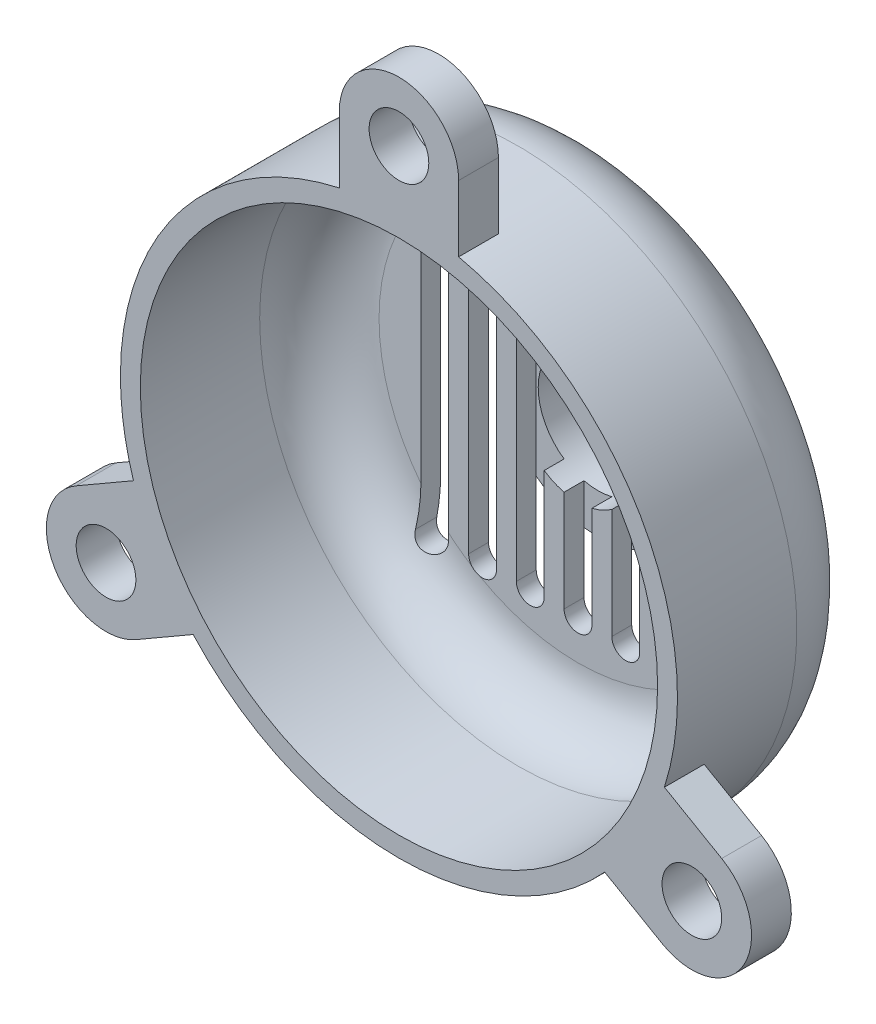
SolidWorks part; units mm, degrees
ref_plane "Front Plane" through (0, 0, 0) normal (0, 0, 1) x (1, 0, 0)
ref_plane "Top Plane" through (0, 0, 0) normal (0, 1, 0) x (1, 0, 0)
ref_plane "Right Plane" through (0, 0, 0) normal (1, 0, 0) x (0, 0, -1)
sketch "Sketch1" plane through (0, 0, 0) normal (0, 1, 0) x (1, 0, 0)
  line L0 (0, 4.1155) -> (0, -4.1155) construction
  line L1 (-7.037, 0) -> (6.2623, 0) construction
  line L2 (0, 0) -> (2.5, 0)
  line L3 (3.5, -1) -> (3.5, -2.5)
  line L4 (0, -0.25) -> (2.5, -0.25)
  line L5 (3.25, -1) -> (3.25, -2.5)
  line L6 (3.25, -2.5) -> (3.5, -2.5)
  line L7 (0, 0) -> (0, -0.25)
  arc A0 (2.5, 0) -> (3.5, -1) centre (2.5, -1) cw
  arc A1 (2.5, -0.25) -> (3.25, -1) centre (2.5, -1) cw
  dimension "D3" = 1
  dimension "D1" = 3.5
  dimension "D2" = 2.5
  dimension "D4" = 2.5
  dimension "D5" = 0.25
revolve "Revolve1" add sketch "Sketch1" angle 360 about L0
sketch "Sketch2" plane through (0, 0, 0) normal (0, 0, -1) x (-1, 0, 0)
  circle A0 centre (0, 0) radius 1.25
  circle A1 centre (0, 0) radius 0.75
  dimension "D1" = 2.5
  dimension "D2" = 1.5
extrude "Boss-Extrude1" add sketch "Sketch2" along normal blind 0.5
sketch "Sketch3" plane through (0, 0, 0) normal (0, 0, -1) x (-1, 0, 0)
  circle A0 centre (0, 0) radius 0.75
  dimension "D1" = 1.5
extrude "Cut-Extrude1" cut sketch "Sketch3" against normal blind 0.5
fillet "Fillet4" radius 0.2 1 edges at (-1.25, 0, -0.5)
sketch "Sketch4" plane through (0, 0, 2.5) normal (0, 0, 1) x (1, 0, 0)
  line L0 (0, 7.8157) -> (0, -6.0608) construction
  line L1 (-8.9879, 0) -> (12.9995, 0) construction
  line L2 (0.75, 4.25) -> (0.75, 3.4187)
  line L3 (-0.75, 4.25) -> (-0.75, 3.4187)
  line L4 (3.3056, -2.7745) -> (2.5857, -2.3589)
  line L5 (4.0556, -1.4755) -> (3.3357, -1.0598)
  line L6 (-4.0556, -1.4755) -> (-3.3357, -1.0598)
  line L7 (-3.3056, -2.7745) -> (-2.5857, -2.3589)
  arc A0 (0.75, 4.25) -> (-0.75, 4.25) centre (0, 4.25) ccw
  circle A1 centre (0, 4.25) radius 0.375
  circle A2 centre (0, 0) radius 4.25 construction
  circle A3 centre (0, 0) radius 3.5 construction
  arc A5 (0.75, 3.4187) -> (-0.75, 3.4187) centre (0, 0) ccw
  arc A6 (3.3056, -2.7745) -> (4.0556, -1.4755) centre (3.6806, -2.125) ccw
  circle A7 centre (3.6806, -2.125) radius 0.375
  arc A8 (2.5857, -2.3589) -> (3.3357, -1.0598) centre (0, 0) ccw
  arc A9 (-4.0556, -1.4755) -> (-3.3056, -2.7745) centre (-3.6806, -2.125) ccw
  circle A10 centre (-3.6806, -2.125) radius 0.375
  arc A11 (-3.3357, -1.0598) -> (-2.5857, -2.3589) centre (0, 0) ccw
  point P31 (0, 0)
  dimension "D1" = 8.5
  dimension "D2" = 0.75
  dimension "D3" = 1.5
  dimension "D4" = 3
extrude "Boss-Extrude2" add sketch "Sketch4" against normal blind 0.5
sketch "Sketch5" plane through (0, 0, 0) normal (0, 0, -1) x (-1, 0, 0)
  line L0 (-1.5179, 0) -> (2.6571, 0) construction
  line L2 (-0.175, 2) -> (-0.175, -2)
  line L4 (0.175, 2) -> (0.175, -2)
  line L5 (0.775, 2) -> (0.775, -2)
  line L6 (0.425, 2) -> (0.425, -2)
  line L7 (1.375, 2) -> (1.375, -2)
  line L8 (1.025, 2) -> (1.025, -2)
  line L9 (1.975, 2) -> (1.975, -2)
  line L10 (1.625, 2) -> (1.625, -2)
  line L11 (-0.425, 2) -> (-0.425, -2)
  line L12 (-0.775, 2) -> (-0.775, -2)
  line L13 (-1.025, 2) -> (-1.025, -2)
  line L14 (-1.375, 2) -> (-1.375, -2)
  line L15 (-1.625, 2) -> (-1.625, -2)
  line L16 (-1.975, 2) -> (-1.975, -2)
  arc A0 (-0.175, 2) -> (0.175, 2) centre (0, 2) cw
  arc A1 (-0.175, -2) -> (0.175, -2) centre (0, -2) ccw
  arc A2 (0.425, 2) -> (0.775, 2) centre (0.6, 2) cw
  arc A3 (0.425, -2) -> (0.775, -2) centre (0.6, -2) ccw
  arc A4 (1.025, 2) -> (1.375, 2) centre (1.2, 2) cw
  arc A5 (1.025, -2) -> (1.375, -2) centre (1.2, -2) ccw
  arc A6 (1.625, 2) -> (1.975, 2) centre (1.8, 2) cw
  arc A7 (1.625, -2) -> (1.975, -2) centre (1.8, -2) ccw
  arc A8 (-0.775, 2) -> (-0.425, 2) centre (-0.6, 2) cw
  arc A9 (-0.775, -2) -> (-0.425, -2) centre (-0.6, -2) ccw
  arc A10 (-1.375, 2) -> (-1.025, 2) centre (-1.2, 2) cw
  arc A11 (-1.375, -2) -> (-1.025, -2) centre (-1.2, -2) ccw
  arc A12 (-1.975, 2) -> (-1.625, 2) centre (-1.8, 2) cw
  arc A13 (-1.975, -2) -> (-1.625, -2) centre (-1.8, -2) ccw
  point P7 (0.175, 0)
  dimension "D3" = 0.175
  dimension "D1" = 0.35
  dimension "D2" = 4
  dimension "D4" = 4
  dimension "D5" = 4
extrude "Cut-Extrude3" cut sketch "Sketch5" against normal through all
